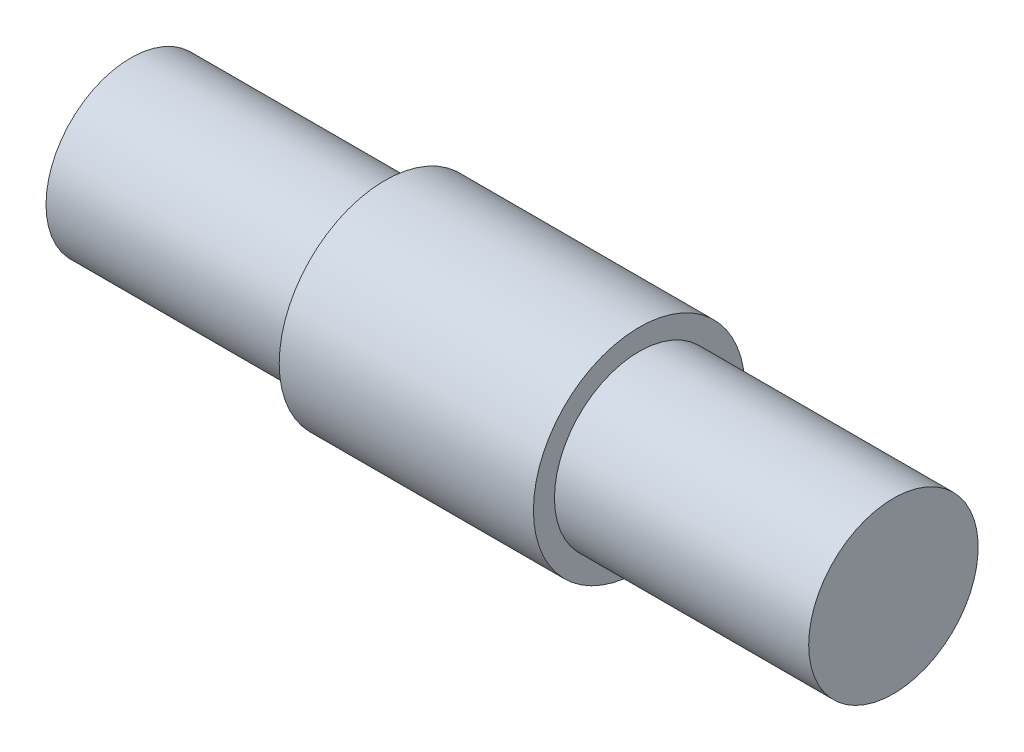
SolidWorks part; units mm, degrees
ref_plane "Front Plane" through (0, 0, 0) normal (0, 0, 1) x (1, 0, 0)
ref_plane "Top Plane" through (0, 0, 0) normal (0, 1, 0) x (1, 0, 0)
ref_plane "Right Plane" through (0, 0, 0) normal (1, 0, 0) x (0, 0, -1)
sketch "Sketch1" plane through (0, 0, 0) normal (0, 0, 1) x (1, 0, 0)
  line L8 (0, 0) -> (28.575, 0)
  line L9 (28.575, 0) -> (28.575, 3.175)
  line L10 (28.575, 3.175) -> (19.05, 3.175)
  line L11 (19.05, 3.175) -> (19.05, 3.9624)
  line L12 (19.05, 3.9624) -> (9.525, 3.9624)
  line L13 (9.525, 3.9624) -> (9.525, 3.175)
  line L14 (9.525, 3.175) -> (0, 3.175)
  line L15 (0, 3.175) -> (0, 0)
  point P8 (0, 0)
  point P10 (0, 0)
  dimension "D1" = 28.575
  dimension "D2" = 9.525
  dimension "D3" = 3.9624
  dimension "D4" = 3.175
revolve "Revolve1" add sketch "Sketch1" angle 360 about L8
